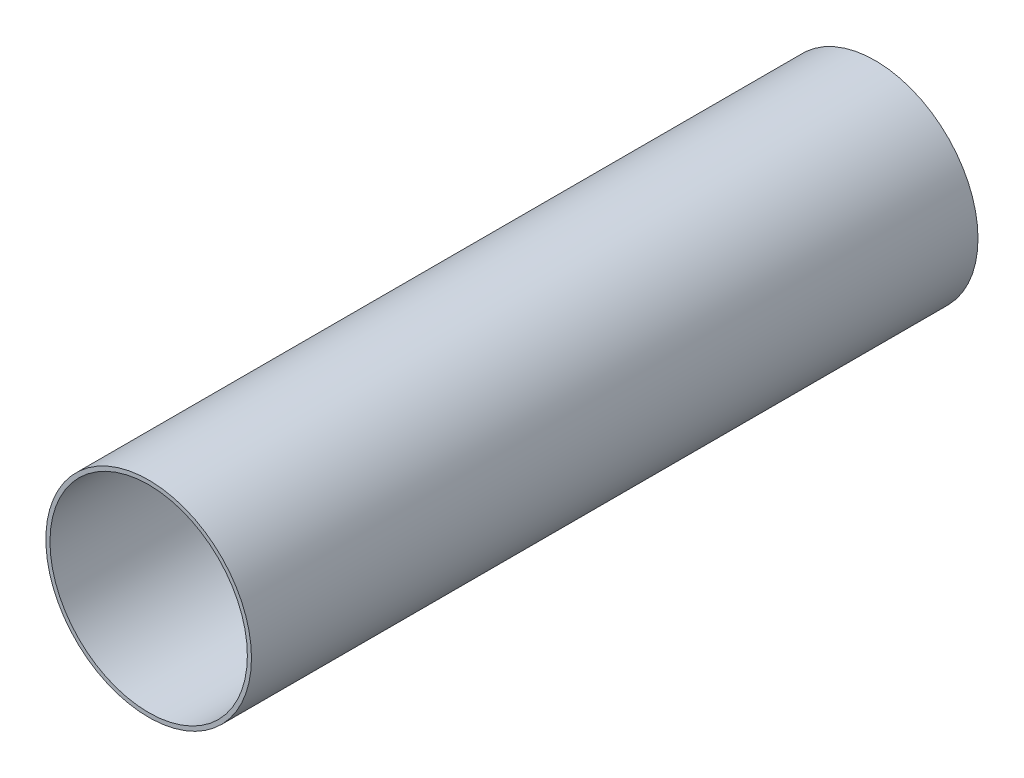
SolidWorks part; units mm, degrees
ref_plane "Front" through (0, 0, 0) normal (0, 0, 1) x (1, 0, 0)
ref_plane "Top" through (0, 0, 0) normal (0, 1, 0) x (1, 0, 0)
ref_plane "Side" through (0, 0, 0) normal (1, 0, 0) x (0, 0, -1)
sketch "PipeSketch" plane through (0, 0, 0) normal (0, 0, 1) x (1, 0, 0)
  circle A0 centre (0, 0) radius 6.35
  circle A1 centre (0, 0) radius 6.096 construction
  dimension "OuterDiameter" = 12.7
  dimension "InnerDiameter" = 12.192
sketch "FilterSketch" plane through (0, 0, 0) normal (0, 0, 1) x (1, 0, 0)
  circle A0 centre (0, 0) radius 6.35 construction
  dimension "NominalDiameter" = 12.7
sketch3d "3DSketch1"
  line L2 (0, 0, 0) -> (0, 0, 44.8711) construction
  line L3 (0, 0, 0) -> (0, 0, 44.8711)
sweep "ThinSweep" add profiles "PipeSketch" path "3DSketch1" parameters "WallThickness"=0.254
ref_plane "Plane1" through (0, 0, 0) normal (0, 0, 1) x (1, 0, 0)
